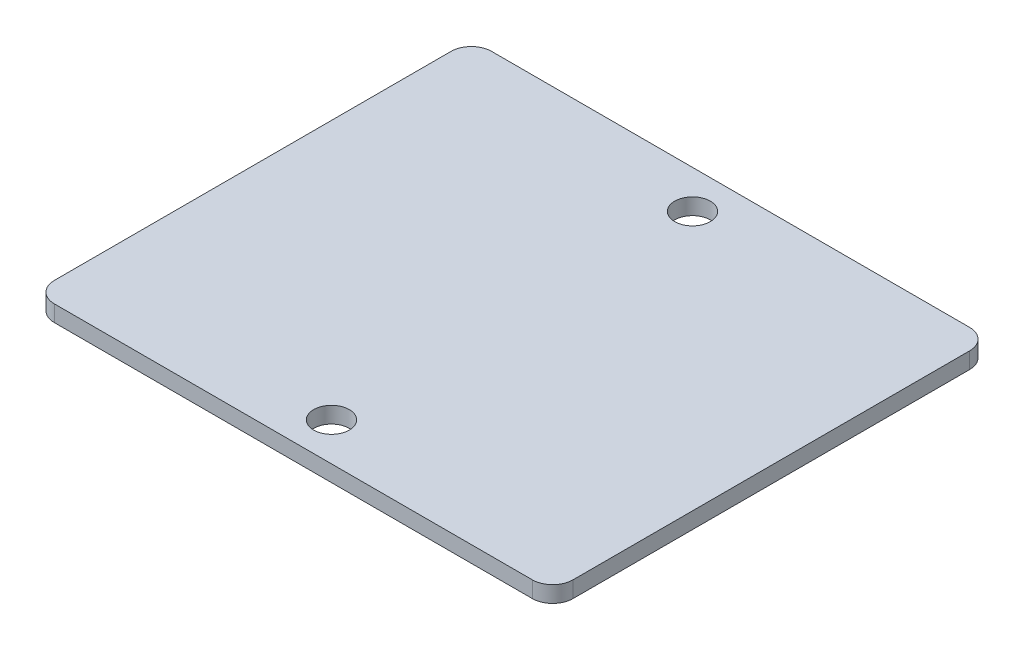
SolidWorks part; units mm, degrees
ref_plane "Front Plane" through (0, 0, 0) normal (0, 0, 1) x (1, 0, 0)
ref_plane "Top Plane" through (0, 0, 0) normal (0, 1, 0) x (1, 0, 0)
ref_plane "Right Plane" through (0, 0, 0) normal (1, 0, 0) x (0, 0, -1)
sketch "Sketch1" plane through (0, 0, 0) normal (0, 1, 0) x (1, 0, 0)
  line L1 (-25.5, -21.5) -> (25.5, -21.5)
  line L2 (-25.5, -21.5) -> (-25.5, 21.5)
  line L3 (-25.5, 21.5) -> (25.5, 21.5)
  line L4 (25.5, -21.5) -> (25.5, 21.5)
  line L5 (-25.5, -21.5) -> (25.5, 21.5) construction
  line L6 (-25.5, 21.5) -> (25.5, -21.5) construction
  circle A0 centre (0, 17.75) radius 1.75
  circle A1 centre (0, -17.75) radius 1.75
  point P0 (0, 0)
  point P10 (-4.5354, 17.75)
  point P11 (0, 0)
  dimension "D3" = 3.5
  dimension "D1" = 51
  dimension "D2" = 43
  dimension "D4" = 3.75
  dimension "D5" = 3.75
extrude "Boss-Extrude1" add sketch "Sketch1" along normal blind 1.6
fillet "Fillet1" radius 2 4 edges at (-25.5, 0.8, -21.5) (-25.5, 0.8, 21.5) (25.5, 0.8, -21.5) (25.5, 0.8, 21.5)
